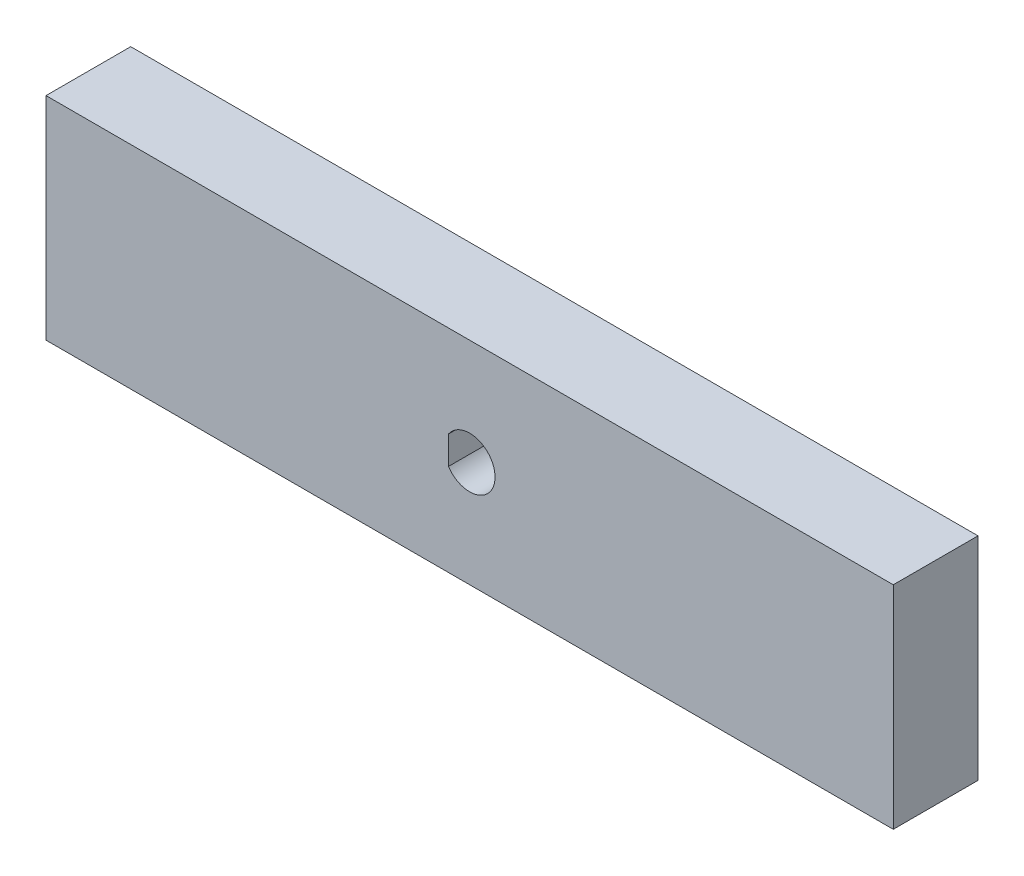
SolidWorks part; units mm, degrees
ref_plane "Front Plane" through (0, 0, 0) normal (0, 0, 1) x (1, 0, 0)
ref_plane "Top Plane" through (0, 0, 0) normal (0, 1, 0) x (1, 0, 0)
ref_plane "Right Plane" through (0, 0, 0) normal (1, 0, 0) x (0, 0, -1)
sketch "Sketch1" plane through (0, 0, 0) normal (0, 0, 1) x (1, 0, 0)
  line L1 (-50, 12.5) -> (50, 12.5)
  line L2 (-50, 12.5) -> (-50, -12.5)
  line L3 (-50, -12.5) -> (50, -12.5)
  line L4 (50, 12.5) -> (50, -12.5)
  point P4 (50, 0)
  point P6 (0, 12.5)
  dimension "D1" = 25
  dimension "D2" = 100
extrude "Boss-Extrude1" add sketch "Sketch1" along normal blind 10
sketch "Sketch2" plane through (0, 0, 10) normal (0, 0, 1) x (1, 0, 0)
  line L0 (-2.5, 1.6583) -> (-2.5, -1.6583)
  line L1 (3, 3.7586) -> (3, -4.9149) construction
  arc A0 (-2.5, -1.6583) -> (-2.5, 1.6583) centre (0, 0) ccw
  dimension "D1" = 6
  dimension "D2" = 5.5
extrude "Cut-Extrude1" cut sketch "Sketch2" against normal blind 10
